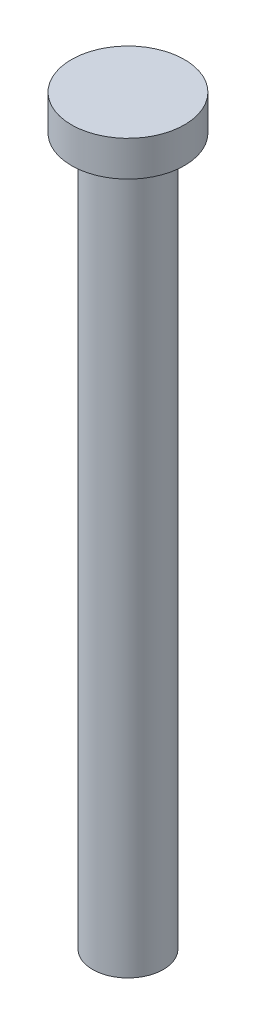
SolidWorks part; units mm, degrees
ref_plane "Plan de face" through (0, 0, 0) normal (0, 0, 1) x (1, 0, 0)
ref_plane "Plan de dessus" through (0, 0, 0) normal (0, 1, 0) x (1, 0, 0)
ref_plane "Plan de droite" through (0, 0, 0) normal (1, 0, 0) x (0, 0, -1)
sketch "Esquisse1" plane through (0, 0, 0) normal (0, 1, 0) x (1, 0, 0)
  circle A0 centre (0, 0) radius 2.5
  dimension "D1" = 5
extrude "BASE" add sketch "Esquisse1" against normal blind 50
sketch "Esquisse2" plane through (0, 0, 0) normal (0, 1, 0) x (1, 0, 0)
  circle A0 centre (0, 0) radius 4
  dimension "D1" = 8
extrude "BOSS TETE" add sketch "Esquisse2" along normal blind 2.5
